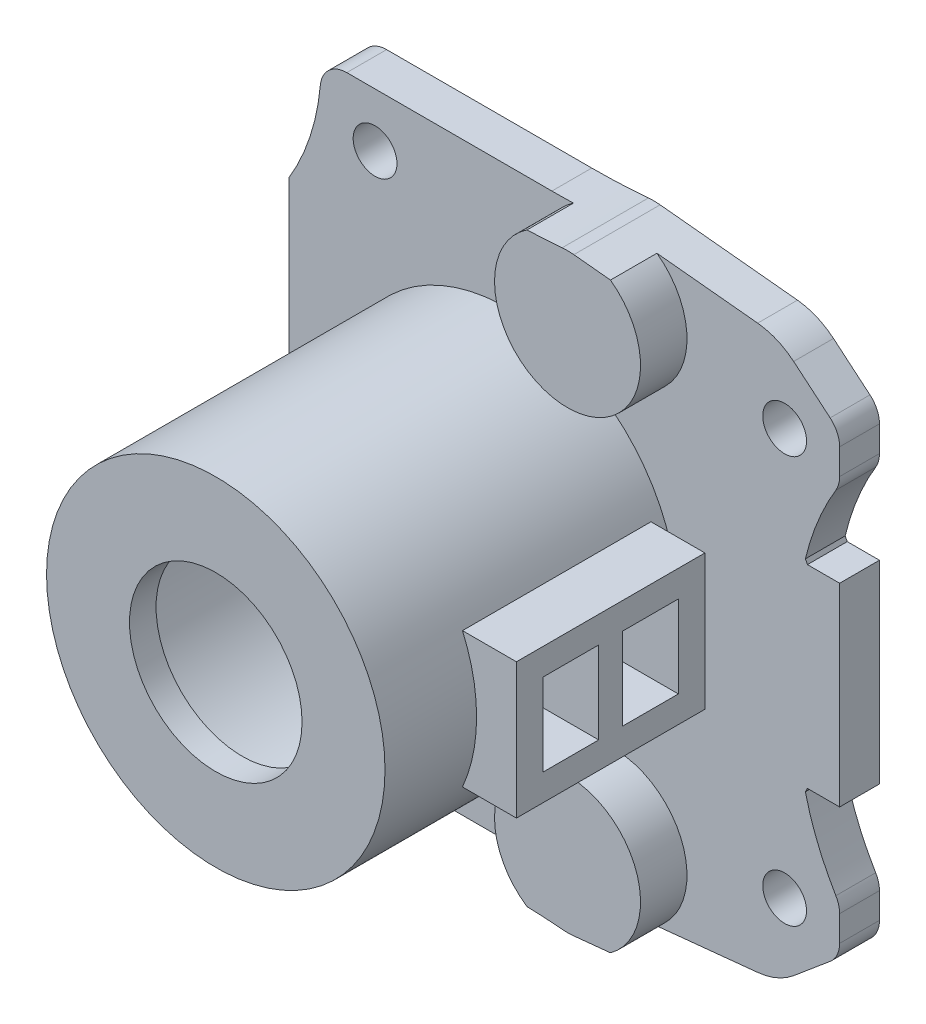
SolidWorks part; units mm, degrees
material "PETG"
ref_plane "Спереди" through (0, 0, 0) normal (0, 0, 1) x (1, 0, 0)
ref_plane "Сверху" through (0, 0, 0) normal (0, 1, 0) x (1, 0, 0)
ref_plane "Справа" through (0, 0, 0) normal (1, 0, 0) x (0, 0, -1)
sketch "Эскиз1" plane through (0, 0, 0) normal (0, 0, 1) x (1, 0, 0)
  line L15 (-12.13, -22.05) -> (6.6362, -22.05)
  line L16 (8.4771, -22.226) -> (18.8245, -21.1813)
  line L17 (21.5362, -20.0368) -> (24.2856, -17.7298)
  line L18 (25, -16.1977) -> (25, -14.2588)
  line L19 (22.4198, -7.6) -> (20.1132, -7.6)
  line L20 (12, -13.7292) -> (12, -17.5)
  line L21 (4, -17.5) -> (4, -13.7292)
  line L22 (4, 13.7292) -> (4, 17.5)
  line L23 (12, 17.5) -> (12, 13.7292)
  line L24 (20.1132, 7.6) -> (22.4198, 7.6)
  line L25 (25, 14.2588) -> (25, 16.1977)
  line L26 (24.2856, 17.7298) -> (21.5362, 20.0368)
  line L27 (18.8245, 21.1813) -> (8.4771, 22.226)
  line L28 (3.3245, 22.05) -> (-12.13, 22.05)
  line L29 (-16.5, 13) -> (-16.5, -13)
  line L30 (-12.13, -22.05) -> (6.6362, -22.05)
  line L31 (8.4771, -22.226) -> (18.8245, -21.1813)
  line L32 (21.5362, -20.0368) -> (24.2856, -17.7298)
  line L33 (25, -16.1977) -> (25, -14.2588)
  line L34 (22.4198, -7.6) -> (20.1132, -7.6)
  line L35 (12, -13.7292) -> (12, -17.5)
  line L36 (4, -17.5) -> (4, -13.7292)
  line L37 (4, 13.7292) -> (4, 17.5)
  line L38 (12, 17.5) -> (12, 13.7292)
  line L39 (20.1132, 7.6) -> (22.4198, 7.6)
  line L40 (25, 14.2588) -> (25, 16.1977)
  line L41 (24.2856, 17.7298) -> (21.5362, 20.0368)
  line L42 (18.8245, 21.1813) -> (8.4771, 22.226)
  line L43 (3.3245, 22.05) -> (-12.13, 22.05)
  line L44 (-16.5, 13) -> (-16.5, -13)
  circle A0 centre (-10, -18) radius 2.05 construction
  circle A1 centre (20.8558, -15.3209) radius 2.05 construction
  circle A2 centre (20.8558, 15.3209) radius 2.05 construction
  circle A3 centre (-10, 18) radius 2.05 construction
  circle A4 centre (-10, -18) radius 2.05
  circle A5 centre (20.8558, -15.3209) radius 2.05
  circle A6 centre (20.8558, 15.3209) radius 2.05
  circle A7 centre (-10, 18) radius 2.05
  arc A20 (6.6362, -22.05) -> (8.4771, -22.226) centre (8, -17.5) ccw
  arc A21 (18.8245, -21.1813) -> (21.5362, -20.0368) centre (18.3222, -16.2066) ccw
  arc A22 (24.2856, -17.7298) -> (25, -16.1977) centre (23, -16.1977) ccw
  arc A23 (25, -14.2588) -> (24.7157, -13.2309) centre (23, -14.2588) ccw
  arc A24 (22.4198, -7.6) -> (24.7157, -13.2309) centre (41.8722, -2.9522) ccw
  arc A25 (12, -13.7292) -> (20.1132, -7.6) centre (8, 0) ccw
  arc A26 (4, -17.5) -> (12, -17.5) centre (8, -17.5) ccw
  arc A27 (4, 13.7292) -> (4, -13.7292) centre (8, 0) ccw
  arc A28 (12, 17.5) -> (4, 17.5) centre (8, 17.5) ccw
  arc A29 (20.1132, 7.6) -> (12, 13.7292) centre (8, 0) ccw
  arc A30 (24.7157, 13.2309) -> (22.4198, 7.6) centre (41.8722, 2.9522) ccw
  arc A31 (24.7157, 13.2309) -> (25, 14.2588) centre (23, 14.2588) ccw
  arc A32 (25, 16.1977) -> (24.2856, 17.7298) centre (23, 16.1977) ccw
  arc A33 (21.5362, 20.0368) -> (18.8245, 21.1813) centre (18.3222, 16.2066) ccw
  arc A34 (8.4771, 22.226) -> (7.5944, 22.2326) centre (8, 17.5) ccw
  arc A35 (3.3245, 22.05) -> (7.5944, 22.2326) centre (3.3245, 72.05) ccw
  arc A36 (-12.13, 22.05) -> (-14.1216, 20.2334) centre (-12.13, 20.05) ccw
  arc A37 (-16.5, 13) -> (-14.1216, 20.2334) centre (-31.05, 21.7919) ccw
  arc A38 (-14.1216, -20.2334) -> (-16.5, -13) centre (-31.05, -21.7919) ccw
  arc A39 (-14.1216, -20.2334) -> (-12.13, -22.05) centre (-12.13, -20.05) ccw
  arc A40 (6.6362, -22.05) -> (8.4771, -22.226) centre (8, -17.5) ccw
  arc A41 (18.8245, -21.1813) -> (21.5362, -20.0368) centre (18.3222, -16.2066) ccw
  arc A42 (24.2856, -17.7298) -> (25, -16.1977) centre (23, -16.1977) ccw
  arc A43 (25, -14.2588) -> (24.7157, -13.2309) centre (23, -14.2588) ccw
  arc A44 (22.4198, -7.6) -> (24.7157, -13.2309) centre (41.8722, -2.9522) ccw
  arc A45 (12, -13.7292) -> (20.1132, -7.6) centre (8, 0) ccw
  arc A46 (4, -17.5) -> (12, -17.5) centre (8, -17.5) ccw
  arc A47 (4, 13.7292) -> (4, -13.7292) centre (8, 0) ccw
  arc A48 (12, 17.5) -> (4, 17.5) centre (8, 17.5) ccw
  arc A49 (20.1132, 7.6) -> (12, 13.7292) centre (8, 0) ccw
  arc A50 (24.7157, 13.2309) -> (22.4198, 7.6) centre (41.8722, 2.9522) ccw
  arc A51 (24.7157, 13.2309) -> (25, 14.2588) centre (23, 14.2588) ccw
  arc A52 (25, 16.1977) -> (24.2856, 17.7298) centre (23, 16.1977) ccw
  arc A53 (21.5362, 20.0368) -> (18.8245, 21.1813) centre (18.3222, 16.2066) ccw
  arc A54 (8.4771, 22.226) -> (7.5944, 22.2326) centre (8, 17.5) ccw
  arc A55 (3.3245, 22.05) -> (7.5944, 22.2326) centre (3.3245, 72.05) ccw
  arc A56 (-12.13, 22.05) -> (-14.1216, 20.2334) centre (-12.13, 20.05) ccw
  arc A57 (-16.5, 13) -> (-14.1216, 20.2334) centre (-31.05, 21.7919) ccw
  arc A58 (-14.1216, -20.2334) -> (-16.5, -13) centre (-31.05, -21.7919) ccw
  arc A59 (-14.1216, -20.2334) -> (-12.13, -22.05) centre (-12.13, -20.05) ccw
  dimension "D1" = 0
extrude "Бобышка-Вытянуть1" add sketch "Эскиз1" along normal blind 3
sketch "Эскиз2" plane through (0, 0, 3) normal (0, 0, 1) x (1, 0, 0)
  line L0 (8, 0) -> (50008.0419, 0) construction
  line L1 (20.1132, 7.6) -> (22.4198, 7.6) construction
  line L2 (22.4198, -7.6) -> (20.1132, -7.6) construction
  line L3 (19.9461, -7.3) -> (25, -7.3) construction
  line L4 (25, -7.3) -> (25, 7.3) construction
  line L5 (25, 7.3) -> (19.9461, 7.3) construction
  line L6 (20.1132, 7.6) -> (22.4198, 7.6)
  line L7 (22.4198, -7.6) -> (20.1132, -7.6)
  line L8 (22.5739, -7.3) -> (25, -7.3)
  line L9 (25, -7.3) -> (25, 7.3)
  line L10 (25, 7.3) -> (22.5739, 7.3)
  line L11 (12, 17.5) -> (12, 13.7292) construction
  line L12 (4, 13.7292) -> (4, 17.5) construction
  line L13 (12, 17.5) -> (12, 13.7292)
  line L14 (4, 13.7292) -> (4, 17.5)
  line L15 (12, -13.7292) -> (12, -17.5) construction
  line L16 (4, -17.5) -> (4, -13.7292) construction
  line L17 (12, -13.7292) -> (12, -17.5)
  line L18 (4, -17.5) -> (4, -13.7292)
  circle A0 centre (0, 0) radius 6
  arc A2 (4, 13.7292) -> (4, -13.7292) centre (8, 0) ccw
  arc A3 (20.1132, 7.6) -> (12, 13.7292) centre (8, 0) ccw construction
  arc A4 (4, 17.5) -> (12, 17.5) centre (8, 17.5) ccw
  arc A5 (4, -17.5) -> (12, -17.5) centre (8, -17.5) cw
  arc A6 (12, -13.7292) -> (20.1132, -7.6) centre (8, 0) ccw
  arc A7 (22.4198, -7.6) -> (22.4198, 7.6) centre (8, 0) ccw construction
  arc A8 (22.4198, -7.6) -> (22.5739, -7.3) centre (8, 0) ccw
  arc A9 (20.1132, 7.6) -> (12, 13.7292) centre (8, 0) ccw
  arc A10 (22.5739, 7.3) -> (22.4198, 7.6) centre (8, 0) ccw
  circle A11 centre (20.8558, -15.3209) radius 2.05 construction
  circle A12 centre (-10, -18) radius 2.05 construction
  circle A13 centre (20.8558, 15.3209) radius 2.05 construction
  circle A14 centre (-10, 18) radius 2.05 construction
  circle A15 centre (20.8558, -15.3209) radius 2.05
  circle A16 centre (-10, -18) radius 2.05
  circle A17 centre (20.8558, 15.3209) radius 2.05
  circle A18 centre (-10, 18) radius 2.05
  circle A19 centre (-10, 18) radius 1.65
  circle A20 centre (20.8558, 15.3209) radius 1.65
  circle A21 centre (20.8558, -15.3209) radius 1.65
  circle A22 centre (-10, -18) radius 1.65
  dimension "D1" = 12
  dimension "D2" = 8
  dimension "D3" = 3.3
extrude "Бобышка-Вытянуть2" add sketch "Эскиз2" against normal up to surface (3 mm away) up to face at (10.5129, 0.6319, 0)
sketch "Эскиз3" plane through (0, 0, 3) normal (0, 0, 1) x (1, 0, 0)
  line L2 (0, 0) -> (50000, 0) construction
  line L4 (18.8245, 21.1813) -> (8.4771, 22.226) construction
  line L5 (11.2357, 21.9475) -> (8.4771, 22.226)
  line L6 (11.2357, -21.9475) -> (8.4771, -22.226)
  circle A0 centre (8, 17.5) radius 4 construction
  circle A1 centre (8, 17.5) radius 4
  arc A11 (4.9493, 22.0764) -> (11.2357, 21.9475) centre (8, 17.5) ccw
  arc A12 (8.4771, 22.226) -> (7.5944, 22.2326) centre (8, 17.5) ccw construction
  arc A13 (3.3245, 22.05) -> (7.5944, 22.2326) centre (3.3245, 72.05) ccw construction
  arc A14 (8.4771, 22.226) -> (7.5944, 22.2326) centre (8, 17.5) ccw
  arc A15 (4.9493, 22.0764) -> (7.5944, 22.2326) centre (3.3245, 72.05) ccw
  arc A16 (4.9493, -22.0764) -> (11.2357, -21.9475) centre (8, -17.5) cw
  circle A17 centre (8, 17.5) radius 5.5 construction
  arc A18 (4.9493, -22.0764) -> (7.5944, -22.2326) centre (3.3245, -72.05) cw
  arc A19 (8.4771, -22.226) -> (7.5944, -22.2326) centre (8, -17.5) cw
  circle A20 centre (8, -17.5) radius 4
  point P15 (13.5, 17.5)
  dimension "D1" = 1.5
extrude "Бобышка-Вытянуть3" add sketch "Эскиз3" along normal blind 2
sketch "Эскиз4" plane through (0, 0, 5) normal (0, 0, 1) x (1, 0, 0)
  line L0 (8.4771, -22.226) -> (11.2357, -21.9475) construction
  line L1 (11.2357, 21.9475) -> (8.4771, 22.226) construction
  line L3 (8.4771, -22.226) -> (11.2357, -21.9475)
  line L5 (11.2357, 21.9475) -> (8.4771, 22.226)
  arc A0 (7.5944, -22.2326) -> (4.9493, -22.0764) centre (3.3245, -72.05) ccw construction
  arc A1 (7.5944, -22.2326) -> (8.4771, -22.226) centre (8, -17.5) ccw construction
  arc A2 (11.2357, -21.9475) -> (4.9493, -22.0764) centre (8, -17.5) ccw construction
  arc A3 (8.4771, 22.226) -> (7.5944, 22.2326) centre (8, 17.5) ccw construction
  arc A4 (4.9493, 22.0764) -> (7.5944, 22.2326) centre (3.3245, 72.05) ccw construction
  arc A5 (4.9493, 22.0764) -> (11.2357, 21.9475) centre (8, 17.5) ccw construction
  arc A9 (7.5944, -22.2326) -> (4.9493, -22.0764) centre (3.3245, -72.05) ccw
  arc A10 (7.5944, -22.2326) -> (8.4771, -22.226) centre (8, -17.5) ccw
  arc A11 (11.2357, -21.9475) -> (4.9493, -22.0764) centre (8, -17.5) ccw
  arc A15 (8.4771, 22.226) -> (7.5944, 22.2326) centre (8, 17.5) ccw
  arc A16 (4.9493, 22.0764) -> (7.5944, 22.2326) centre (3.3245, 72.05) ccw
  arc A17 (4.9493, 22.0764) -> (11.2357, 21.9475) centre (8, 17.5) ccw
extrude "Бобышка-Вытянуть4" add sketch "Эскиз4" along normal blind 1.5
sketch "Эскиз5" plane through (0, 0, 3) normal (0, 0, 1) x (1, 0, 0)
  circle A1 centre (0, 0) radius 10.75
  circle A2 centre (0, 0) radius 12.75
  dimension "D1" = 21.5
  dimension "D2" = 2
extrude "Бобышка-Вытянуть5" add sketch "Эскиз5" along normal blind 20
sketch "Эскиз6" plane through (0, 0, 3) normal (0, 0, 1) x (1, 0, 0)
  circle A1 centre (0, 0) radius 10.75
  circle A2 centre (0, 0) radius 10.75
  dimension "D1" = 0
extrude "Вырез-Вытянуть1" cut sketch "Эскиз6" against normal up to surface (3 mm away) up to face at (12, -17.5, 0)
sketch "Эскиз8" plane through (0, 0, 23) normal (0, 0, 1) x (1, 0, 0)
  circle A0 centre (0, 0) radius 6.5
  circle A1 centre (0, 0) radius 12.75
  circle A2 centre (0, 0) radius 12.75
  dimension "D2" = 13
  dimension "D1" = 0
extrude "Бобышка-Вытянуть6" add sketch "Эскиз8" along normal blind 2
sketch "Эскиз9" plane through (0, 0, 0) normal (1, 0, 0) x (0, 0, -1)
  line L0 (0, 0) -> (50000, 0) construction
  line L1 (-3, -7.3) -> (-3, 7.3) construction
  line L2 (-5.9, 3.1) -> (-10.1, 3.1)
  line L3 (-5.9, 3.1) -> (-5.9, -3.1)
  line L4 (-5.9, -3.1) -> (-10.1, -3.1)
  line L5 (-10.1, 3.1) -> (-10.1, -3.1)
  line L6 (-5.9, 3.1) -> (-10.1, -3.1) construction
  line L7 (-5.9, -3.1) -> (-10.1, 3.1) construction
  line L8 (-11.9, 3.1) -> (-16.1, 3.1)
  line L9 (-11.9, 3.1) -> (-11.9, -3.1)
  line L10 (-11.9, -3.1) -> (-16.1, -3.1)
  line L11 (-16.1, 3.1) -> (-16.1, -3.1)
  line L12 (-11.9, 3.1) -> (-16.1, -3.1) construction
  line L13 (-11.9, -3.1) -> (-16.1, 3.1) construction
  point P3 (-8, 0)
  point P8 (-14, 0)
  point P13 (-42.5105, 0)
  dimension "D1" = 6
  dimension "D2" = 4.2
  dimension "D3" = 6.2
  dimension "D4" = 5
extrude "Вырез-Вытянуть2" cut sketch "Эскиз9" along normal up to surface (12.3674 mm away)
ref_plane "Плоскость1" through (10.75, 0, 0) normal (-1, 0, 0) x (0, 0, 1)
sketch "Эскиз10" plane through (10.75, 0, 0) normal (-1, 0, 0) x (0, 0, 1)
  line L0 (16.1, 3.1) -> (16.1, -3.1) construction
  line L1 (16.1, -3.1) -> (11.9, -3.1) construction
  line L2 (11.9, -3.1) -> (11.9, 3.1) construction
  line L3 (11.9, 3.1) -> (16.1, 3.1) construction
  line L4 (10.1, 3.1) -> (10.1, -3.1) construction
  line L9 (16.1, 3.1) -> (16.1, -3.1)
  line L10 (16.1, -3.1) -> (11.9, -3.1)
  line L15 (11.9, -3.1) -> (11.9, 3.1)
  line L16 (11.9, 3.1) -> (16.1, 3.1)
  line L17 (10.1, -3.1) -> (5.9, -3.1) construction
  line L18 (5.9, -3.1) -> (5.9, 3.1) construction
  line L19 (5.9, 3.1) -> (10.1, 3.1) construction
  line L20 (10.1, 3.1) -> (10.1, -3.1)
  line L21 (10.1, -3.1) -> (5.9, -3.1)
  line L22 (5.9, -3.1) -> (5.9, 3.1)
  line L23 (5.9, 3.1) -> (10.1, 3.1)
  line L27 (3.9, -5.1) -> (3.9, 5.1)
  line L29 (18.1, 5.1) -> (18.1, -5.1)
  line L32 (9.9, -5.1) -> (9.9, 5.1) construction
  line L33 (12.1, 5.1) -> (12.1, -5.1) construction
  line L34 (3.9, 5.1) -> (18.1, 5.1)
  line L35 (12.1, -5.1) -> (3.9, -5.1) construction
  line L36 (3.9, 5.1) -> (12.1, 5.1) construction
  line L37 (9.9, 5.1) -> (18.1, 5.1) construction
  line L38 (18.1, -5.1) -> (9.9, -5.1) construction
  line L39 (3.9, -5.1) -> (18.1, -5.1)
  dimension "D1" = 2
extrude "Бобышка-Вытянуть9" add sketch "Эскиз10" against normal blind 5
